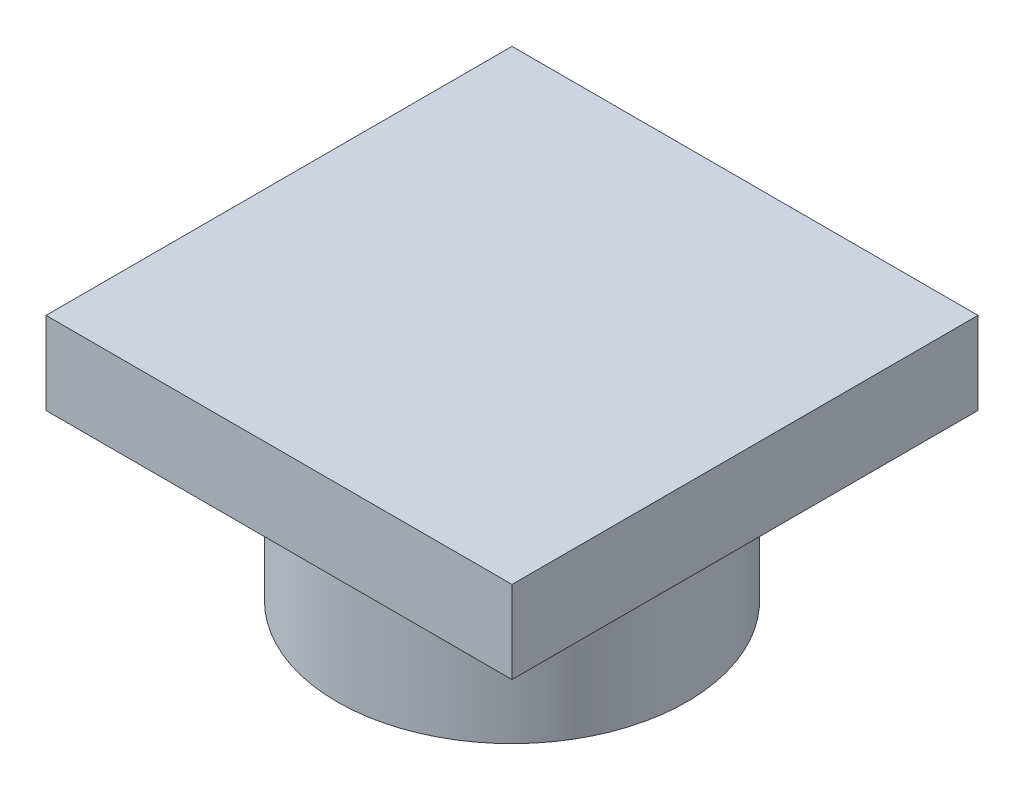
SolidWorks part; units mm, degrees
ref_plane "Front Plane" through (0, 0, 0) normal (0, 0, 1) x (1, 0, 0)
ref_plane "Top Plane" through (0, 0, 0) normal (0, 1, 0) x (1, 0, 0)
ref_plane "Right Plane" through (0, 0, 0) normal (1, 0, 0) x (0, 0, -1)
sketch "Sketch1" plane through (0, 0, 0) normal (0, 1, 0) x (1, 0, 0)
  circle A0 centre (0, 0) radius 4.25
  dimension "D1" = 8.5
extrude "Boss-Extrude1" add sketch "Sketch1" along normal blind 4
sketch "Sketch2" plane through (0, 4, 0) normal (0, 1, 0) x (1, 0, 0)
  line L0 (0, 0) -> (13.6781, 0)
  line L1 (-5.6569, 5.6569) -> (5.6569, 5.6569)
  line L2 (-5.6569, 5.6569) -> (-5.6569, -5.6569)
  line L3 (-5.6569, -5.6569) -> (5.6569, -5.6569)
  line L4 (5.6569, 5.6569) -> (5.6569, -5.6569)
  line L5 (-5.6569, 5.6569) -> (5.6569, -5.6569) construction
  line L6 (-5.6569, -5.6569) -> (5.6569, 5.6569) construction
  circle A0 centre (0, 0) radius 8
  dimension "D1" = 16
  dimension "D2" = 45
extrude "Boss-Extrude2" add sketch "Sketch2" along normal blind 2
sketch "Sketch3" plane through (0, 0, 0) normal (0, -1, 0) x (1, 0, 0)
  circle A0 centre (0, 0) radius 4.1
  dimension "D1" = 8.2
extrude "Cut-Extrude1" cut sketch "Sketch3" against normal blind 2
